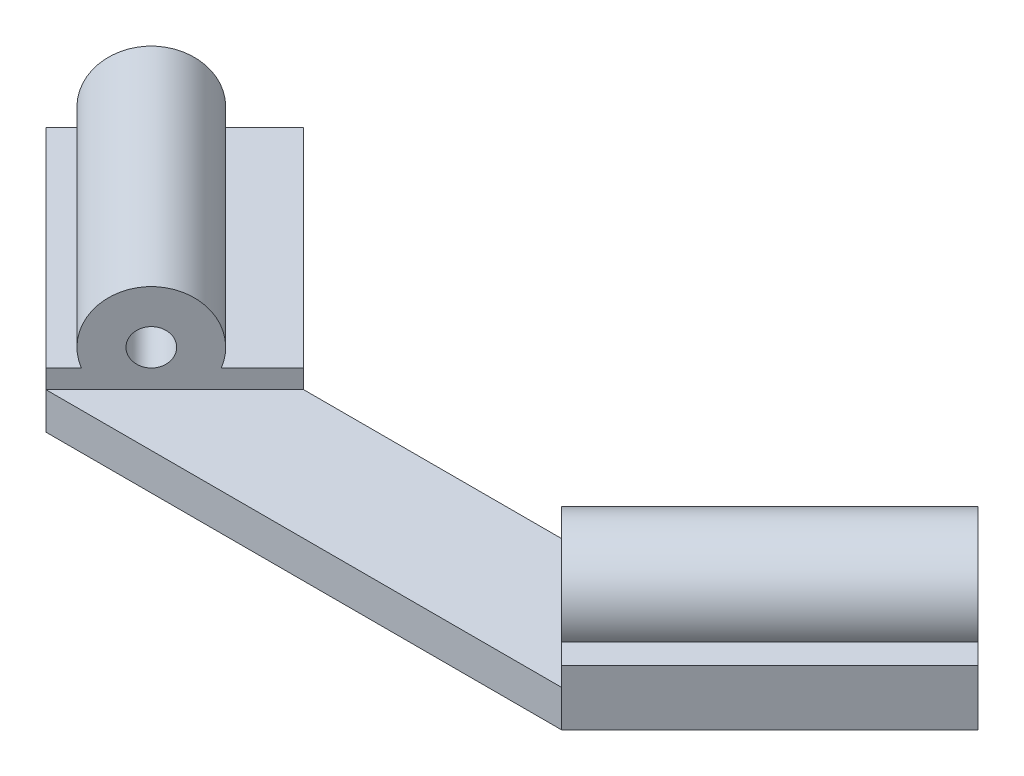
SolidWorks part; units mm, degrees
ref_plane "Front Plane" through (0, 0, 0) normal (0, 0, 1) x (1, 0, 0)
ref_plane "Top Plane" through (0, 0, 0) normal (0, 1, 0) x (1, 0, 0)
ref_plane "Right Plane" through (0, 0, 0) normal (1, 0, 0) x (0, 0, -1)
sketch "Trapezoid1" plane through (0, 0, 0) normal (0, 1, 0) x (1, 0, 0)
  line L0 (-114.3356, -37.1761) -> (-96.8356, -19.6761)
  line L1 (-96.8356, -19.6761) -> (-61.8356, -19.6761)
  line L3 (-114.3356, -37.1761) -> (-44.3356, -37.1761)
  line L7 (-44.3356, -37.1761) -> (-61.8356, -19.6761)
  point P0 (0, 0)
  dimension "D1" = 45
  dimension "D2" = 45
  dimension "D3" = 70
  dimension "D4" = 35
extrude "Boss-Extrude1" add sketch "Trapezoid1" along normal blind 5 from offset 4
sketch "AntennaHolster1" plane through (-40.7559, 0, 40.7559) normal (0.7071, 0, -0.7071) x (-0.7071, 0, -0.7071)
  line L1 (5.0626, 4) -> (29.8113, 4)
  line L2 (5.0626, 4) -> (5.0626, 11.55)
  line L3 (5.0626, 11.55) -> (29.8113, 11.55)
  line L4 (29.8113, 4) -> (29.8113, 11.55)
  circle A0 centre (15.7076, 13.9863) radius 2.4363
  arc A1 (22.4231, 11.55) -> (8.9921, 11.55) centre (15.7076, 13.9863) ccw
  line M7 (29.8113, 4) -> (29.8113, 9)
  line M8 (29.8113, 9) -> (5.0626, 9)
  line M9 (5.0626, 9) -> (5.0626, 4)
  dimension "D1" = 7.55
extrude "Boss-Extrude2" add sketch "AntennaHolster1" along normal blind 40 contours L4 L3 L2 M8 | L3 A1 A0 | L1 M9 M7 M8
sketch "AntennaHolster2" plane through (-38.5798, 0, -38.5798) normal (-0.7071, 0, -0.7071) x (-0.7071, 0, 0.7071)
  line L1 (82.3862, 4) -> (107.135, 4)
  line L2 (82.3862, 4) -> (82.3862, 11.55)
  line L3 (82.3862, 11.55) -> (107.135, 11.55)
  line L4 (107.135, 4) -> (107.135, 11.55)
  circle A0 centre (97.0214, 13.9862) radius 2.4362
  arc A1 (103.7369, 11.55) -> (90.3059, 11.55) centre (97.0214, 13.9862) ccw
  line M7 (107.135, 4) -> (107.135, 9)
  line M8 (107.135, 9) -> (82.3862, 9)
  line M9 (82.3862, 9) -> (82.3862, 4)
  dimension "D1" = 7.55
extrude "Boss-Extrude3" add sketch "AntennaHolster2" along normal blind 40 contours L4 L3 L2 M8 | L3 A1 A0 | L1 M9 M7 M8
